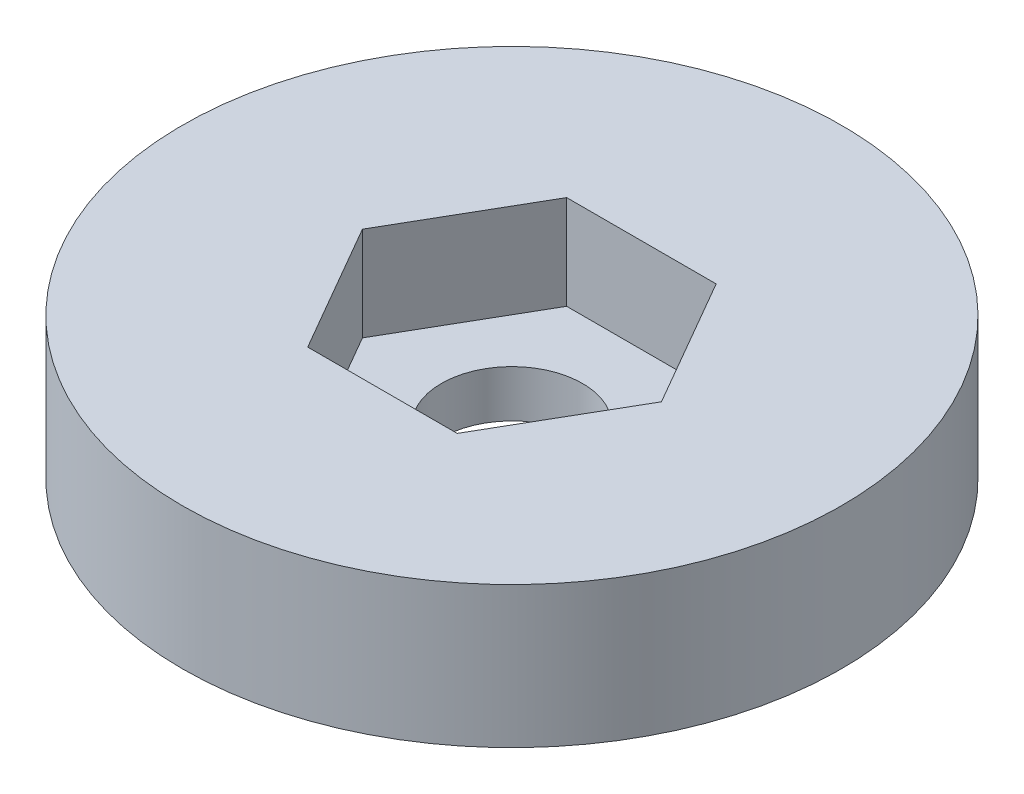
SolidWorks part; units mm, degrees
ref_plane "Спереди" through (0, 0, 0) normal (0, 0, 1) x (1, 0, 0)
ref_plane "Сверху" through (0, 0, 0) normal (0, 1, 0) x (1, 0, 0)
ref_plane "Справа" through (0, 0, 0) normal (1, 0, 0) x (0, 0, -1)
sketch "Эскиз1" plane through (0, 0, 0) normal (0, 1, 0) x (1, 0, 0)
  circle A0 centre (0, 0) radius 7
  circle A1 centre (0, 0) radius 1.5
  dimension "D1" = 14
  dimension "D2" = 3
extrude "Бобышка-Вытянуть1" add sketch "Эскиз1" along normal blind 3
sketch "Эскиз2" plane through (0, 3, 0) normal (0, 1, 0) x (1, 0, 0)
  line L1 (1.5877, 2.75) -> (-1.5877, 2.75)
  line L2 (-1.5877, 2.75) -> (-3.1754, 0)
  line L3 (-3.1754, 0) -> (-1.5877, -2.75)
  line L4 (-1.5877, -2.75) -> (1.5877, -2.75)
  line L5 (1.5877, -2.75) -> (3.1754, 0)
  line L6 (3.1754, 0) -> (1.5877, 2.75)
  circle A0 centre (0, 0) radius 2.75 construction
  dimension "D1" = 5.5
extrude "Вырез-Вытянуть1" cut sketch "Эскиз2" against normal blind 2
